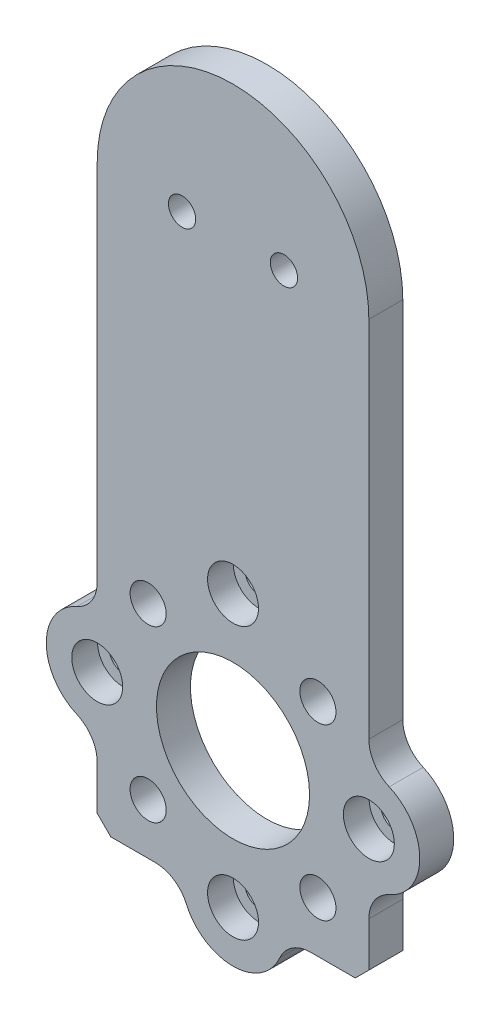
SolidWorks part; units mm, degrees
material "6061 Alloy"
ref_plane "Front Plane" through (0, 0, 0) normal (0, 0, 1) x (1, 0, 0)
ref_plane "Top Plane" through (0, 0, 0) normal (0, 1, 0) x (1, 0, 0)
ref_plane "Right Plane" through (0, 0, 0) normal (1, 0, 0) x (0, 0, -1)
sketch "Sketch1" plane through (0, 0, 0) normal (0, 0, 1) x (1, 0, 0)
  line L1 (0, 0) -> (15.875, 0)
  line L6 (-9.525, 25.4) -> (60.325, 25.4) construction
  line L7 (25.4, -9.525) -> (25.4, 25.4) construction
  line L14 (0, 0) -> (0, 15.875)
  line L15 (50.8, 107.95) -> (50.8, 34.925)
  line L16 (0, 34.925) -> (0, 107.95)
  line L17 (50.8, 15.875) -> (50.8, 0)
  line L18 (34.925, 0) -> (50.8, 0)
  arc A0 (50.8, 107.95) -> (0, 107.95) centre (25.4, 107.95) ccw
  circle A4 centre (41.275, 9.525) radius 3.3782
  circle A5 centre (9.525, 9.525) radius 3.3782
  circle A6 centre (9.525, 41.275) radius 3.3782
  circle A7 centre (41.275, 41.275) radius 3.3782
  arc A8 (50.8, 15.875) -> (50.8, 34.925) centre (50.8, 25.4) ccw
  arc A9 (0, 15.875) -> (0, 34.925) centre (0, 25.4) cw
  arc A10 (34.925, 0) -> (15.875, 0) centre (25.4, 0) cw
  circle A11 centre (25.4, 25.4) radius 14.3129
  dimension "D1" = 107.95
  dimension "D7" = 6.7564
  dimension "D8" = 9.525
  dimension "D9" = 15.875
  dimension "D11" = 25.4
  dimension "D12" = 28.6258
  dimension "D2" = 31.75
  dimension "D3" = 9.525
  dimension "D4" = 31.75
  dimension "D5" = 50.8
  dimension "D6" = 9.525
  dimension "D10" = 15.875
extrude "Boss-Extrude1" add sketch "Sketch1" along normal blind 6.35
hole_wizard "CBORE for #10 Socket Head Cap Screw1" positions "Sketch3" profile "Sketch4" counterbore size "#10" standard "ANSI Inch" end condition through all
sketch "Sketch3" plane through (0, 0, 6.35) normal (0, 0, 1) x (1, 0, 0)
  line L0 (34.925, 0) -> (50.8, 0) construction
  circle A0 centre (25.4, 25.4) radius 25.4 construction
  point P0 (0, 25.4)
  point P3 (50.8, 25.4)
  point P6 (25.4, 0)
  point P14 (25.4, 50.8)
  dimension "D1" = 50.8
  dimension "D2" = 25.4
sketch "Sketch4" plane through (0, 25.4, 6.35) normal (1, 0, 0) x (0, -1, 0)
  line L0 (0, 0) -> (0, 6.35)
  line L1 (0, 6.35) -> (2.5527, 6.35)
  line L3 (2.5527, 6.35) -> (2.5527, 4.826)
  line L4 (2.5527, 4.826) -> (4.7625, 4.826)
  line L5 (4.7625, 4.826) -> (4.7625, 0)
  line L7 (4.7625, 0) -> (0, 0)
  line L11 (0, -6.35) -> (0, 107.95) construction
  dimension "Thru Hole Dia." = 5.1054
  dimension "Thru Hole Depth" = 6.35
  dimension "C'Bore Dia." = 9.525
  dimension "C'Bore Depth" = 4.826
hole_wizard "1/4-20 Tapped Hole2" positions "Sketch8" profile "Sketch9" tap size "1/4-20" standard "ANSI Inch" end condition through all
sketch "Sketch8" plane through (0, 0, 0) normal (0, 0, 1) x (1, 0, 0)
  line L5 (34.925, 107.95) -> (15.875, 107.95) construction
  arc A2 (50.8, 107.95) -> (0, 107.95) centre (25.4, 107.95) ccw construction
  point P0 (15.875, 107.95)
  point P2 (34.925, 107.95)
  point P26 (25.4, 107.95)
  dimension "D1" = 19.05
sketch "Sketch9" plane through (15.875, 107.95, 0) normal (1, 0, 0) x (0, 1, 0)
  line L0 (0, 0) -> (0, 6.35)
  line L1 (0, 6.35) -> (2.5527, 6.35)
  line L2 (2.5527, 6.35) -> (2.5527, 0)
  line L5 (2.5527, 0) -> (0, 0)
  line L11 (0, -6.35) -> (0, 107.95) construction
  dimension "Thru Tap Drill Dia." = 5.1054
  dimension "Thru Tap Drill Depth" = 6.35
cosmetic thread "Hole Thread1" parameters "D1"=12.954, "D2"=6.1054
cosmetic thread "Hole Thread2" parameters "D1"=12.954, "D2"=6.1054
fillet "Fillet1" radius 6.35 6 edges at (0, 15.875, 3.175) (0, 34.925, 3.175) (50.8, 15.875, 3.175) (34.925, 0, 3.175) (15.875, 0, 3.175) (50.8, 34.925, 3.175)
chamfer "Chamfer1" distance 2.54 angle 45 2 edges at (0, 0, 3.175) (50.8, 0, 3.175)
